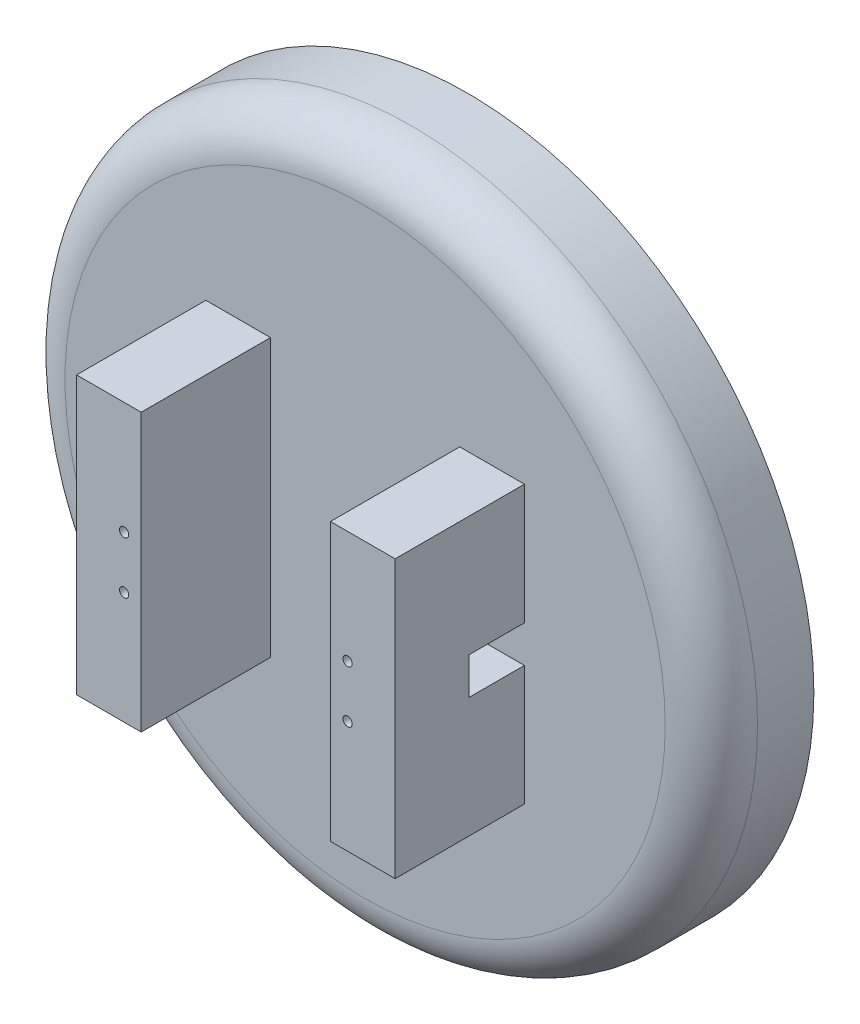
SolidWorks part; units mm, degrees
material "Plastique personnalisé"
ref_plane "Plan de face" through (0, 0, 0) normal (0, 0, 1) x (1, 0, 0)
ref_plane "Plan de dessus" through (0, 0, 0) normal (0, 1, 0) x (1, 0, 0)
ref_plane "Plan de droite" through (0, 0, 0) normal (1, 0, 0) x (0, 0, -1)
sketch "Esquisse1" plane through (0, 0, 0) normal (0, 0, 1) x (1, 0, 0)
  circle A0 centre (0, 0) radius 75
  dimension "D1" = 150
extrude "Boss.-Extru.1" add sketch "Esquisse1" along normal blind 22.2
fillet "Congé1" radius 10 1 edges at (75, 0, 22.2)
sketch "Esquisse2" plane through (0, 0, 22.2) normal (0, 0, 1) x (1, 0, 0)
  line L0 (-20.5, 30) -> (20.5, -30) construction
  line L2 (-20.5, 30) -> (-20.5, -30)
  line L4 (20.5, 30) -> (20.5, -30)
  line L5 (-34.5, 30) -> (-34.5, -30)
  line L6 (-34.5, 30) -> (-20.5, 30)
  line L7 (-34.5, -30) -> (-20.5, -30)
  line L8 (20.5, 30) -> (34.5, 30)
  line L9 (34.5, 30) -> (34.5, -30)
  line L10 (34.5, -30) -> (20.5, -30)
  line L11 (-20.5, -30) -> (20.5, -30) construction
  dimension "D1" = 60
  dimension "D2" = 41
  dimension "D3" = 14
  dimension "D4" = 14
  dimension "D5" = 60
extrude "Boss.-Extru.2" add sketch "Esquisse2" along normal blind 28
sketch "Esquisse3" plane through (0, 0, 50.2) normal (0, 0, 1) x (1, 0, 0)
  line L0 (-34.5, 0) -> (34.5, 0) construction
  line L1 (-34.5, 30) -> (-34.5, -30) construction
  line L2 (34.5, -30) -> (34.5, 30) construction
  line L3 (-20.5, 0) -> (-34.5, 0) construction
  line L4 (-20.5, -30) -> (-20.5, 30) construction
  line L5 (-24.2, 5.65) -> (-24.2, -5.65) construction
  line L6 (0, 65) -> (0, -65) construction
  line L7 (24.2, 5.65) -> (24.2, -5.65) construction
  circle A0 centre (-24.2, 5.65) radius 1
  circle A4 centre (-24.2, -5.65) radius 1
  circle A5 centre (0, 0) radius 65 construction
  circle A6 centre (24.2, -5.65) radius 1
  circle A7 centre (24.2, 5.65) radius 1
  point P9 (-24.2, 0)
  dimension "D1" = 2
  dimension "D2" = 3.7
  dimension "D3" = 5.65
extrude "Enlèv. mat.-Extru.1" cut sketch "Esquisse3" against normal blind 10
sketch "Esquisse5" plane through (0, 0, 0) normal (1, 0, 0) x (0, 0, -1)
  line L1 (-22.2, -4) -> (-34.2, -4)
  line L2 (-22.2, -4) -> (-22.2, 4)
  line L3 (-22.2, 4) -> (-34.2, 4)
  line L4 (-34.2, -4) -> (-34.2, 4)
  dimension "D1" = 22.2
  dimension "D2" = 4
  dimension "D3" = 34.2
  dimension "D4" = 4
extrude "Passage cable MG995" cut sketch "Esquisse5" along normal through all
